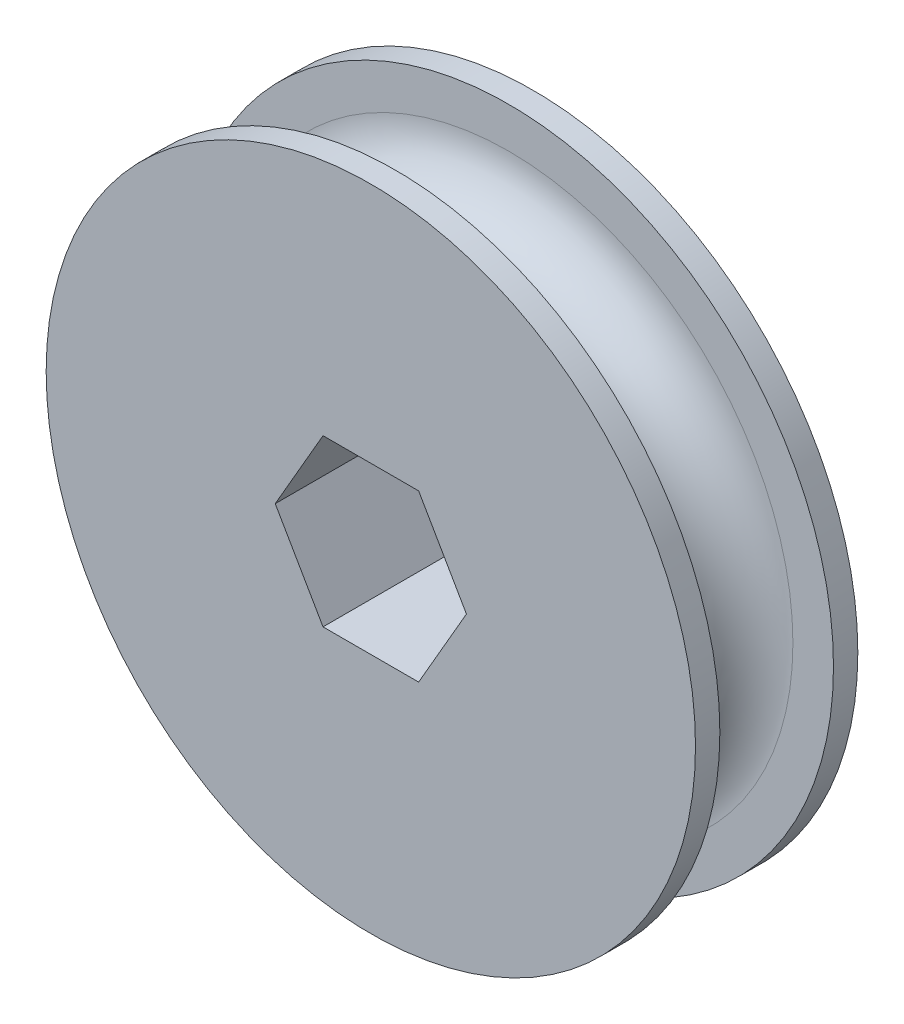
SolidWorks part; units mm, degrees
ref_plane "Front Plane" through (0, 0, 0) normal (0, 0, 1) x (1, 0, 0)
ref_plane "Top Plane" through (0, 0, 0) normal (0, 1, 0) x (1, 0, 0)
ref_plane "Right Plane" through (0, 0, 0) normal (1, 0, 0) x (0, 0, -1)
sketch "Sketch1" plane through (0, 0, 0) normal (0, 0, 1) x (1, 0, 0)
  circle A0 centre (0, 0) radius 25.4
  dimension "D1" = 50.8
extrude "Boss-Extrude1" add sketch "Sketch1" along normal mid plane 12.7
sketch "Sketch3" plane through (0, 0, 0) normal (0, 1, 0) x (1, 0, 0)
  line L0 (-25.4, 6.35) -> (-25.4, -6.35) construction
  line L1 (-25.4, 4.445) -> (-25.4, -4.445)
  line L2 (-22.225, 4.445) -> (-25.4, 4.445)
  line L3 (-22.225, -4.445) -> (-25.4, -4.445)
  arc A0 (-22.225, -4.445) -> (-22.225, 4.445) centre (-22.225, 0) ccw
  dimension "D1" = 8.89
  dimension "D2" = 3.175
ref_axis "Axis1" through (0, 0, 17.1197) along (0, 0, -1)
revolve "Cut-Revolve1" cut sketch "Sketch3" angle 360 about axis through (0, 0, 17.1197) along (0, 0, -1)
sketch "Sketch4" plane through (0, 0, -6.35) normal (0, 0, -1) x (-1, 0, 0)
  line L0 (7.479, 0) -> (3.7395, 6.477)
  line L1 (3.7395, 6.477) -> (-3.7395, 6.477)
  line L2 (-3.7395, 6.477) -> (-7.479, 0)
  line L3 (-7.479, 0) -> (-3.7395, -6.477)
  line L4 (-3.7395, -6.477) -> (3.7395, -6.477)
  line L5 (3.7395, -6.477) -> (7.479, 0)
  point P2 (0, 6.477)
  dimension "D1" = 12.954
  dimension "D2" = 12.954
  dimension "D3" = 12.954
  dimension "D4" = 6.477
  dimension "D5" = 120
extrude "Cut-Extrude1" cut sketch "Sketch4" against normal through all
